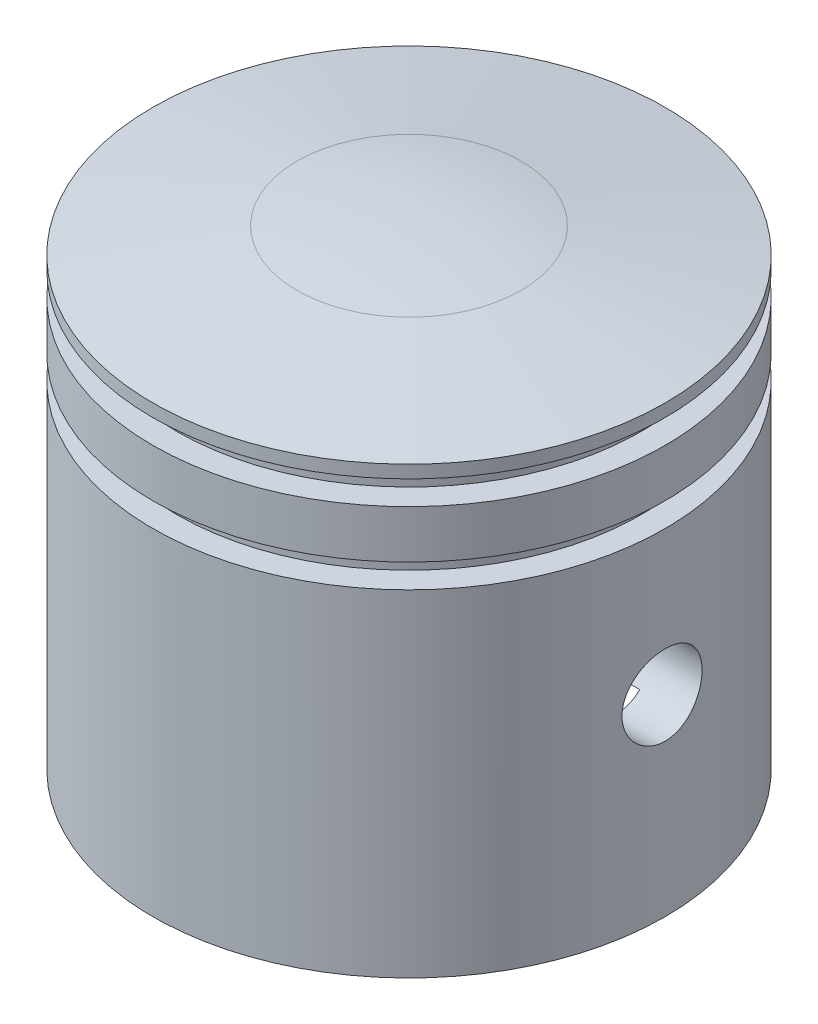
SolidWorks part; units mm, degrees
ref_plane "Front Plane" through (0, 0, 0) normal (0, 0, 1) x (1, 0, 0)
ref_plane "Top Plane" through (0, 0, 0) normal (0, 1, 0) x (1, 0, 0)
ref_plane "Right Plane" through (0, 0, 0) normal (1, 0, 0) x (0, 0, -1)
sketch "Sketch1" plane through (0, 0, 0) normal (0, 0, 1) x (1, 0, 0)
  line L0 (0, 0) -> (16, 0)
  line L1 (16, 0) -> (16, 27.7958)
  line L4 (0, 30) -> (0, 0)
  line L5 (7, 29.3827) -> (16, 27.7958)
  line L7 (0, 30) -> (24.0274, 30) construction
  arc A0 (0, 30) -> (7, 29.3827) centre (0, -10) cw
  point P7 (0, 0)
  point P9 (0, 0)
  dimension "D4" = 40
  dimension "D5" = 40
  dimension "D1" = 16
  dimension "D2" = 30
  dimension "D3" = 10
  dimension "D6" = 7
revolve "Revolve1" add sketch "Sketch1" angle 360 about L4
sketch "Sketch2" plane through (0, 0, 0) normal (0, 0, 1) x (1, 0, 0)
  line L0 (0, 0) -> (0, 31.5114) construction
  line L1 (-16, 0) -> (16, 0) construction
  line L2 (18.091, 27) -> (14.5, 27)
  line L3 (18.091, 27) -> (18.091, 25.5)
  line L4 (18.091, 25.5) -> (14.5, 25.5)
  line L5 (14.5, 27) -> (14.5, 25.5)
  line L6 (17.234, 22.5) -> (14.5, 22.5)
  line L7 (17.234, 22.5) -> (17.234, 21)
  line L8 (17.234, 21) -> (14.5, 21)
  line L9 (14.5, 22.5) -> (14.5, 21)
  dimension "D1" = 1.5
  dimension "D2" = 1.5
  dimension "D3" = 3
  dimension "D4" = 21
  dimension "D5" = 14.5
revolve "Cut-Revolve1" cut sketch "Sketch2" angle 360 about L0
sketch "Sketch3" plane through (0, 0, 0) normal (0, -1, 0) x (1, 0, 0)
  circle A0 centre (0, 0) radius 10
  dimension "D1" = 20
extrude "Cut-Extrude1" cut sketch "Sketch3" against normal blind 24
sketch "Sketch4" plane through (0, 0, 0) normal (0, -1, 0) x (-1, 0, 0)
  circle A0 centre (0, 0) radius 13
  dimension "D1" = 26
extrude "Cut-Extrude2" cut sketch "Sketch4" against normal blind 10
sketch "Sketch5" plane through (0, 0, 0) normal (1, 0, 0) x (0, 0, -1)
  circle A0 centre (0, 12) radius 2.5
  point P2 (0, 0)
  dimension "D1" = 5
  dimension "D2" = 12
extrude "Cut-Extrude3" cut sketch "Sketch5" against normal through all and the other way through all
